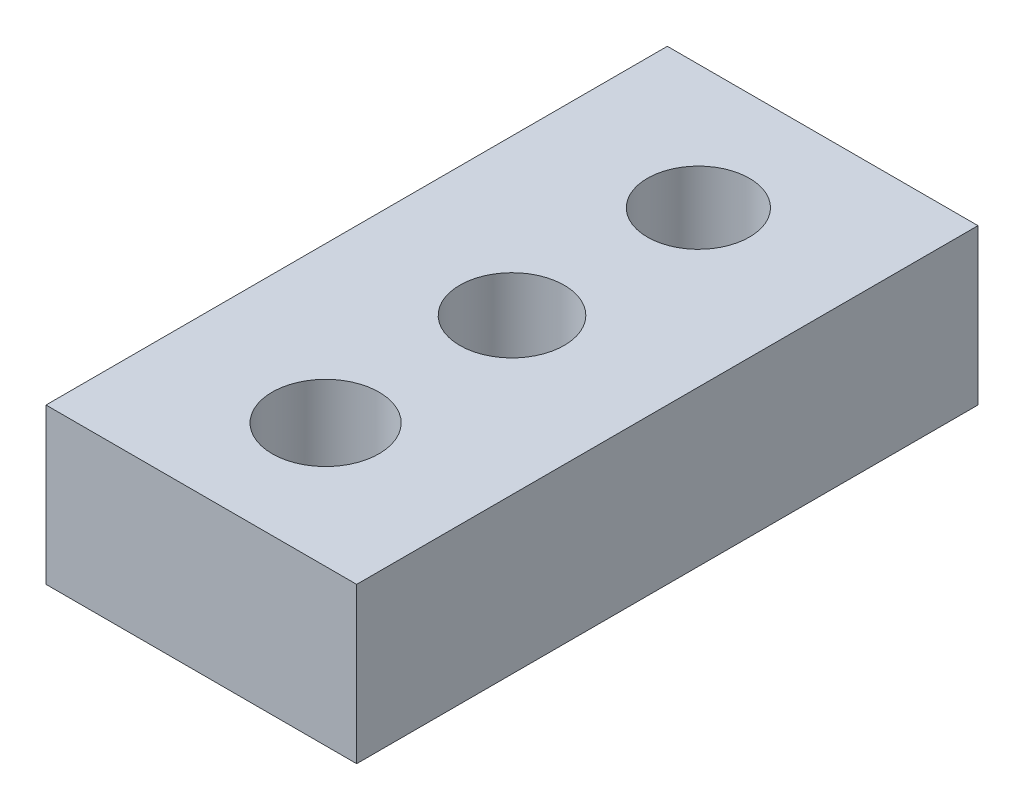
SolidWorks part; units mm, degrees
ref_plane "Front Plane" through (0, 0, 0) normal (0, 0, 1) x (1, 0, 0)
ref_plane "Top Plane" through (0, 0, 0) normal (0, 1, 0) x (1, 0, 0)
ref_plane "Right Plane" through (0, 0, 0) normal (1, 0, 0) x (0, 0, -1)
sketch "Sketch1" plane through (0, 0, 0) normal (0, 1, 0) x (1, 0, 0)
  line L1 (-6.35, -12.7) -> (6.35, -12.7)
  line L2 (-6.35, -12.7) -> (-6.35, 12.7)
  line L3 (-6.35, 12.7) -> (6.35, 12.7)
  line L4 (6.35, -12.7) -> (6.35, 12.7)
  line L5 (-6.35, -12.7) -> (6.35, 12.7) construction
  line L6 (-6.35, 12.7) -> (6.35, -12.7) construction
  point P0 (0, 0)
  dimension "D1" = 12.7
  dimension "D2" = 25.4
extrude "Boss-Extrude1" add sketch "Sketch1" along normal blind 6.35
hole_wizard "Ø1.0 mm Dowel Holes1" positions "Sketch7" profile "Sketch9" hole size "Ø1.0" standard "ANSI Metric"
sketch "Sketch7" plane through (0, 6.35, 0) normal (0, 1, 0) x (1, 0, 0)
  point P0 (0, 7.62)
  dimension "D1" = 7.62
sketch "Sketch9" plane through (0, 6.35, -7.62) normal (1, 0, 0) x (0, 0, 1)
  line L0 (0, 0) -> (0, 9.1268)
  line L1 (0, 9.1268) -> (2.085, 7.874)
  line L2 (2.085, 7.874) -> (2.085, 0)
  line L5 (2.085, 0) -> (0, 0)
  line L10 (0, 9.1268) -> (-2.085, 7.874) construction
  line L11 (0, -6.35) -> (0, 107.95) construction
  dimension "Hole Dia." = 4.17
  dimension "Hole Depth" = 7.874
  dimension "Drill Angle" = 118
hole_wizard "Ø1.0 mm Dowel Holes2" positions "Sketch10" profile "Sketch11" hole size "Ø1.0" standard "ANSI Metric"
sketch "Sketch10" plane through (0, 6.35, 0) normal (0, 1, 0) x (1, 0, 0)
  point P0 (0, 0)
sketch "Sketch11" plane through (0, 6.35, 0) normal (1, 0, 0) x (0, 0, 1)
  line L0 (0, 0) -> (0, 9.1568)
  line L1 (0, 9.1568) -> (2.135, 7.874)
  line L2 (2.135, 7.874) -> (2.135, 0)
  line L5 (2.135, 0) -> (0, 0)
  line L10 (0, 9.1568) -> (-2.135, 7.874) construction
  line L11 (0, -6.35) -> (0, 107.95) construction
  dimension "Hole Dia." = 4.27
  dimension "Hole Depth" = 7.874
  dimension "Drill Angle" = 118
hole_wizard "Ø1.0 mm Dowel Holes3" positions "Sketch12" profile "Sketch13" hole size "Ø1.0" standard "ANSI Metric"
sketch "Sketch12" plane through (0, 6.35, 0) normal (0, 1, 0) x (1, 0, 0)
  point P0 (0, -7.62)
  dimension "D1" = 7.62
sketch "Sketch13" plane through (0, 6.35, 7.62) normal (1, 0, 0) x (0, 0, 1)
  line L0 (0, 0) -> (0, 9.1869)
  line L1 (0, 9.1869) -> (2.185, 7.874)
  line L2 (2.185, 7.874) -> (2.185, 0)
  line L5 (2.185, 0) -> (0, 0)
  line L10 (0, 9.1869) -> (-2.185, 7.874) construction
  line L11 (0, -6.35) -> (0, 107.95) construction
  dimension "Hole Dia." = 4.37
  dimension "Hole Depth" = 7.874
  dimension "Drill Angle" = 118
